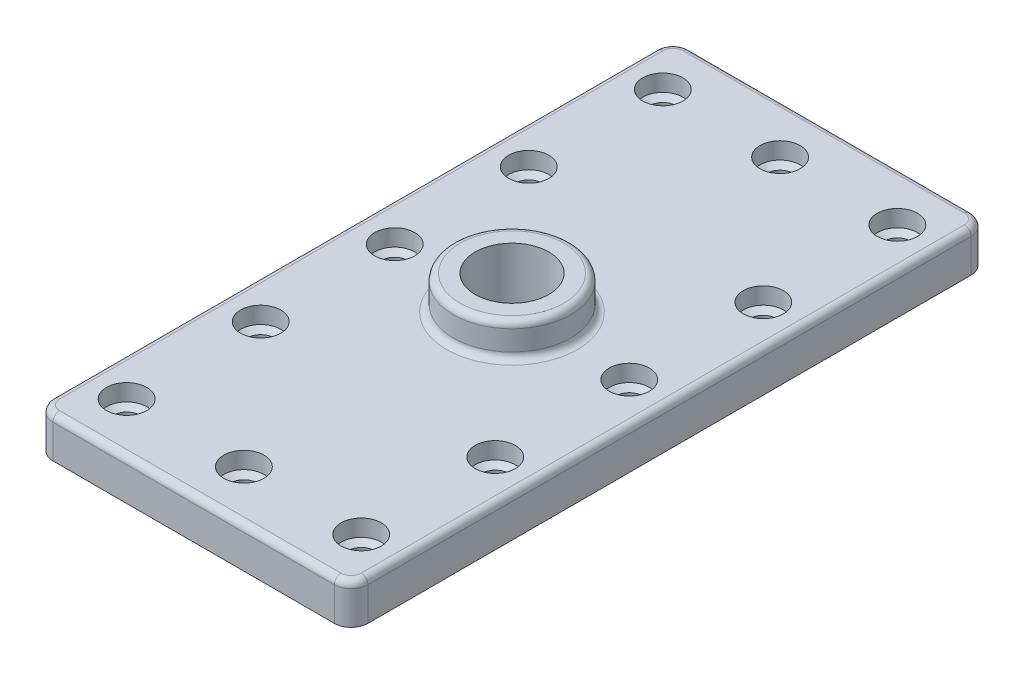
SolidWorks part; units mm, degrees
ref_plane "Front" through (0, 0, 0) normal (0, 0, 1) x (1, 0, 0)
ref_plane "Top" through (0, 0, 0) normal (0, 1, 0) x (1, 0, 0)
ref_plane "Right" through (0, 0, 0) normal (1, 0, 0) x (0, 0, -1)
sketch "Sketch1" plane through (0, 0, 0) normal (0, 1, 0) x (1, 0, 0)
  line L0 (-47, 95) -> (47, -95) construction
  line L1 (-47, -95) -> (47, -95)
  line L2 (-47, -95) -> (-47, 95)
  line L3 (-47, 95) -> (47, 95)
  line L4 (47, -95) -> (47, 95)
  dimension "D1" = 190
  dimension "D2" = 94
extrude "plate" add sketch "Sketch1" along normal blind 12
sketch "Sketch2" plane through (0, 12, 0) normal (0, 1, 0) x (-1, 0, 0)
  circle A0 centre (0, 0) radius 17.5
  dimension "D1" = 35
extrude "boss" add sketch "Sketch2" along normal blind 10
sketch "Sketch3" plane through (0, 22, 0) normal (0, 1, 0) x (-1, 0, 0)
  circle A0 centre (0, 0) radius 11
  dimension "D1" = 22
extrude "center hole" cut sketch "Sketch3" against normal through all
hole_wizard "pattern hole" positions "Sketch5" profile "Sketch4" legacy end condition through all
sketch "Sketch5" plane through (0, 12, 0) normal (0, 1, 0) x (-1, 0, 0)
  line L0 (47, 95) -> (-47, 95) construction
  line L1 (47, -95) -> (47, 95) construction
  point P0 (35, 80)
  dimension "D1" = 15
  dimension "D2" = 12
sketch "Sketch4" plane through (-35, 12, 80) normal (1, 0, 0) x (0, 0, 1)
  line L0 (0, 0) -> (0, 12)
  line L1 (0, 12) -> (4, 12)
  line L2 (4, 12) -> (4, 6.2017)
  line L3 (4, 6.2017) -> (6, 5)
  line L4 (6, 5) -> (6, 0)
  line L5 (6, 0) -> (0, 0)
  line L6 (0, -6.13) -> (0, 109.2824) construction
  line L7 (-4, 6.2017) -> (-6, 5) construction
  line L8 (0, 12) -> (-4, 12) construction
  dimension "Diameter" = 8
  dimension "Depth" = 12
  dimension "C-Drill Diameter" = 12
  dimension "C-Drill Depth" = 5
  dimension "C-Drill Angle" = 118
fillet "R5" radius 5 4 edges at (-47, 6, -95) (47, 6, -95) (47, 6, 95) (-47, 6, 95)
fillet "R2" radius 2 10 edges at (0, 12, -17.5) (0, 22, 17.5) (47, 12, 0) (0, 12, 95) (-47, 12, 0) (0, 12, -95) (45.5355, 12, -93.5355) (-45.5355, 12, -93.5355) (-45.5355, 12, 93.5355) (45.5355, 12, 93.5355)
pattern_linear "LPattern2" count 3 spacing 35 along (1, 0, 0) count 5 spacing 40 along (0, 0, -1) skipping (1, 1), (1, 2), (1, 3) of "pattern hole"
